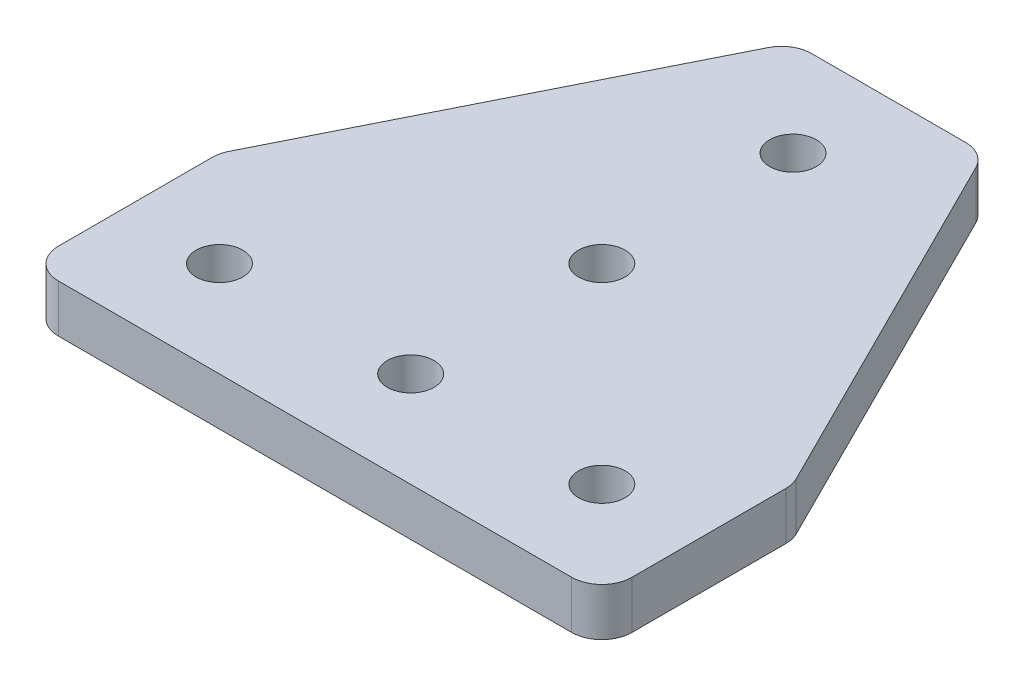
SolidWorks part; units mm, degrees
ref_plane "Front Plane" through (0, 0, 0) normal (0, 0, 1) x (1, 0, 0)
ref_plane "Top Plane" through (0, 0, 0) normal (0, 1, 0) x (1, 0, 0)
ref_plane "Right Plane" through (0, 0, 0) normal (1, 0, 0) x (0, 0, -1)
sketch "Sketch1" plane through (0, 0, 0) normal (0, 1, 0) x (1, 0, 0)
  line L0 (0, 0) -> (0, 25.4) construction
  line L1 (0, 25.4) -> (0, 50.8) construction
  line L2 (0, 0) -> (25.4, 0) construction
  line L3 (0, 0) -> (-25.4, 0) construction
  line L4 (0, -12.7) -> (-38.1, -12.7)
  line L5 (-38.1, -12.7) -> (-38.1, 12.7)
  line L6 (-38.1, 12.7) -> (-12.7, 63.5)
  line L7 (-12.7, 63.5) -> (12.7, 63.5)
  line L8 (12.7, 63.5) -> (38.1, 12.7)
  line L9 (38.1, 12.7) -> (38.1, -12.7)
  line L10 (38.1, -12.7) -> (0, -12.7)
  line L11 (0, 50.8) -> (0, 63.5) construction
  line L12 (0, -12.7) -> (0, 0) construction
  line L13 (-25.4, 0) -> (-38.1, 0) construction
  circle A0 centre (0, 50.8) radius 3.1
  circle A1 centre (0, 25.4) radius 3.1
  circle A2 centre (25.4, 0) radius 3.1
  circle A3 centre (0, 0) radius 3.1
  circle A4 centre (-25.4, 0) radius 3.1
  dimension "D2" = 6.2
  dimension "D1" = 25.4
  dimension "D3" = 25.4
  dimension "D4" = 76.2
  dimension "D5" = 25.4
  dimension "D6" = 38.1
extrude "Boss-Extrude1" add sketch "Sketch1" along normal blind 6.35
fillet "Fillet1" radius 4 6 edges at (12.7, 3.175, -63.5) (-12.7, 3.175, -63.5) (-38.1, 3.175, -12.7) (-38.1, 3.175, 12.7) (38.1, 3.175, 12.7) (38.1, 3.175, -12.7)
